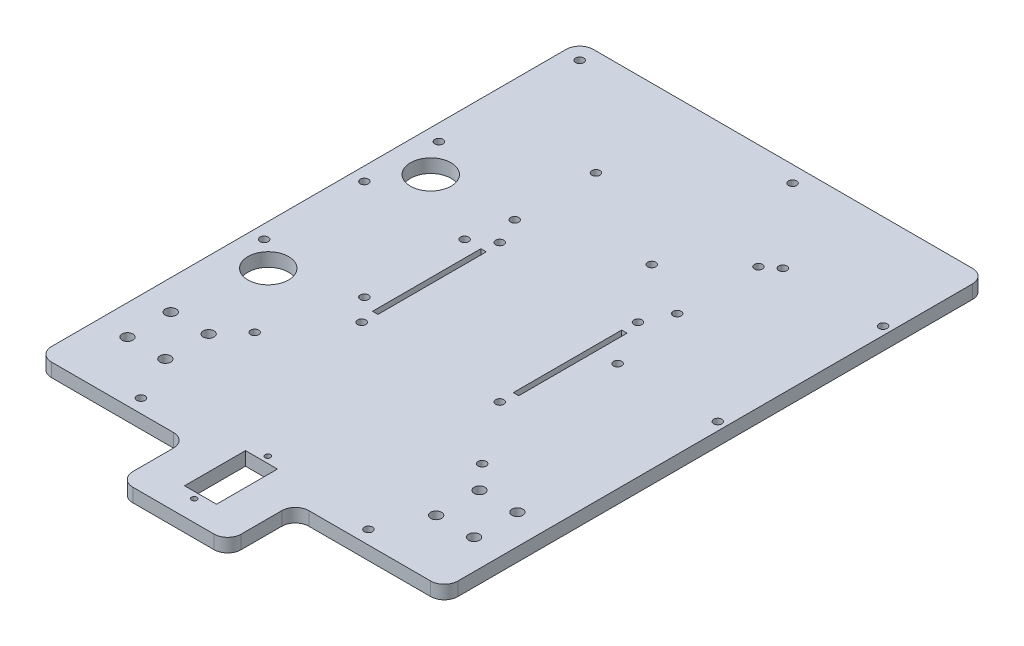
SolidWorks part; units mm, degrees
ref_plane "前视基准面" through (0, 0, 0) normal (0, 0, 1) x (1, 0, 0)
ref_plane "上视基准面" through (0, 0, 0) normal (0, 1, 0) x (1, 0, 0)
ref_plane "右视基准面" through (0, 0, 0) normal (1, 0, 0) x (0, 0, -1)
sketch "草图1" plane through (0, 0, 0) normal (0, 1, 0) x (1, 0, 0)
  line L1 (0, 0) -> (150, 0)
  line L2 (0, 0) -> (0, 100)
  line L3 (0, 200) -> (150, 200)
  line L4 (150, 0) -> (150, 100)
  line L7 (75, 200) -> (75, 0) construction
  line L11 (0, 200) -> (0, 100)
  line L12 (150, 200) -> (150, 100)
  dimension "D1" = 150
  dimension "D2" = 200
extrude "凸台-拉伸1" add sketch "草图1" along normal blind 5
sketch "草图3" plane through (0, 5, 0) normal (0, 1, 0) x (1, 0, 0)
  line L0 (55, 0) -> (55, -25)
  line L1 (55, -25) -> (95, -25)
  line L2 (95, -25) -> (95, 0)
  line L3 (0, 0) -> (150, 0) construction
  line L4 (75, 0) -> (75, -43.4314) construction
  line L5 (55, 0) -> (95, 0)
  line L6 (0, 200) -> (0, 0) construction
  line L7 (150, 0) -> (150, 200) construction
  dimension "D1" = 25
  dimension "D2" = 40
extrude "凸台-拉伸2" add sketch "草图3" against normal blind 5
sketch "草图2" plane through (0, 5, 0) normal (0, 1, 0) x (1, 0, 0)
  line L0 (75, 200) -> (75, 0) construction
  line L1 (150, 200) -> (0, 200) construction
  line L2 (0, 0) -> (55, 0) construction
  line L3 (0, 200) -> (0, 0) construction
  line L4 (102, 75.5) -> (100, 75.5)
  line L6 (150, 0) -> (150, 200) construction
  line L7 (56.8805, 170) -> (99.4606, 170) construction
  line L8 (11, 38) -> (25, 38) construction
  line L9 (25, 38) -> (25, 22) construction
  line L10 (25, 22) -> (11, 22) construction
  line L11 (11, 22) -> (11, 38) construction
  line L12 (4, 30) -> (20, 30) construction
  line L13 (69.1, 7.5) -> (80.9, 7.5)
  line L14 (69.1, 7.5) -> (69.1, -15)
  line L15 (69.1, -15) -> (80.9, -15)
  line L16 (80.9, 7.5) -> (80.9, -15)
  line L18 (-36.7512, 95.5) -> (181.7462, 95.5) construction
  line L21 (33, 47) -> (117, 47) construction
  line L22 (150, 200) -> (0, 200) construction
  line L23 (110, 165) -> (147, 165) construction
  line L24 (110, 165) -> (110, 104) construction
  line L25 (110, 104) -> (147, 104) construction
  line L26 (147, 165) -> (147, 104) construction
  line L27 (5, 115.5) -> (42, 115.5) construction
  line L28 (5, 115.5) -> (5, 78.5) construction
  line L29 (5, 78.5) -> (42, 78.5) construction
  line L30 (42, 115.5) -> (42, 78.5) construction
  line L31 (6, 194) -> (84.6, 194) construction
  line L32 (6, 194) -> (6, 142) construction
  line L33 (6, 142) -> (84.6, 142) construction
  line L34 (84.6, 194) -> (84.6, 142) construction
  line L35 (33, 47) -> (33, 5) construction
  line L36 (33, 5) -> (117, 5) construction
  line L37 (117, 47) -> (117, 5) construction
  line L38 (48, 115.5) -> (50, 115.5)
  line L39 (48, 115.5) -> (48, 75.5)
  line L40 (48, 75.5) -> (50, 75.5)
  line L41 (50, 115.5) -> (50, 75.5)
  line L42 (100, 115.5) -> (100, 75.5)
  line L43 (102, 115.5) -> (100, 115.5)
  line L44 (102, 115.5) -> (102, 75.5)
  line L45 (105, 161) -> (105, 131) construction
  line L46 (0, 0) -> (55, 0) construction
  circle A0 centre (11, 38) radius 2
  circle A1 centre (25, 38) radius 2
  circle A2 centre (11, 22) radius 2
  circle A3 centre (25, 22) radius 2
  circle A4 centre (125, 22) radius 2
  circle A5 centre (139, 22) radius 2
  circle A6 centre (139, 38) radius 2
  circle A7 centre (125, 38) radius 2
  circle A8 centre (75, -17.35) radius 1
  circle A9 centre (75, 9.85) radius 1
  circle A14 centre (49.5, 70) radius 1.5
  circle A15 centre (49.5, 121) radius 1.5
  circle A16 centre (100.5, 121) radius 1.5
  circle A17 centre (100.5, 70) radius 1.5
  circle A26 centre (110, 165) radius 1.5
  circle A27 centre (147, 165) radius 1.5
  circle A28 centre (110, 104) radius 1.5
  circle A29 centre (147, 104) radius 1.5
  circle A30 centre (5, 115.5) radius 1.5
  circle A31 centre (42, 115.5) radius 1.5
  circle A32 centre (42, 78.5) radius 1.5
  circle A33 centre (5, 78.5) radius 1.5
  circle A34 centre (6, 194) radius 1.5
  circle A35 centre (84.6, 194) radius 1.5
  circle A36 centre (84.6, 142) radius 1.5
  circle A37 centre (6, 142) radius 1.5
  circle A38 centre (45, 131) radius 1.5
  circle A39 centre (105, 131) radius 1.5
  circle A40 centre (33, 5) radius 1.5
  circle A41 centre (33, 47) radius 1.5
  circle A42 centre (117, 47) radius 1.5
  circle A43 centre (117, 5) radius 1.5
  circle A44 centre (105, 161) radius 1.5
  circle A45 centre (45, 161) radius 1.5
  circle A46 centre (15, 70) radius 7.5
  circle A47 centre (15, 130) radius 7.5
  point P104 (15.2092, 61.2481)
  dimension "D1" = 4
  dimension "D2" = 14
  dimension "D8" = 2
  dimension "D9" = 2
  dimension "D10" = 2.35
  dimension "D11" = 2.35
  dimension "D15" = 3
  dimension "D16" = 51
  dimension "D17" = 51
  dimension "D19" = 35
  dimension "D20" = 3
  dimension "D21" = 70
  dimension "D27" = 3
  dimension "D31" = 60
  dimension "D43" = 3
  dimension "D45" = 15
  dimension "D46" = 15
  dimension "D48" = 70
  dimension "D49" = 70
  dimension "D50" = 15
  dimension "D3" = 16
  dimension "D4" = 50
  dimension "D5" = 30
  dimension "D6" = 22.5
  dimension "D7" = 11.8
  dimension "D12" = 37
  dimension "D13" = 37
  dimension "D14" = 170
  dimension "D18" = 70
  dimension "D22" = 17
  dimension "D23" = 78.6
  dimension "D24" = 61
  dimension "D25" = 37
  dimension "D26" = 35
  dimension "D28" = 52
  dimension "D29" = 6
  dimension "D30" = 6
  dimension "D32" = 10
  dimension "D33" = 42
  dimension "D34" = 84
  dimension "D35" = 5
  dimension "D36" = 42
  dimension "D37" = 15
  dimension "D38" = 25
  dimension "D39" = 2
  dimension "D40" = 20
  dimension "D41" = 20
  dimension "D42" = 30
  dimension "D44" = 60
  dimension "D47" = 15
extrude "切除-拉伸1" cut sketch "草图2" against normal blind 10
fillet "圆角2" radius 5 8 edges at (150, 2.5, -200) (150, 2.5, 0) (95, 2.5, 0) (95, 2.5, 25) (55, 2.5, 25) (55, 2.5, 0) (0, 2.5, 0) (0, 2.5, -200)
